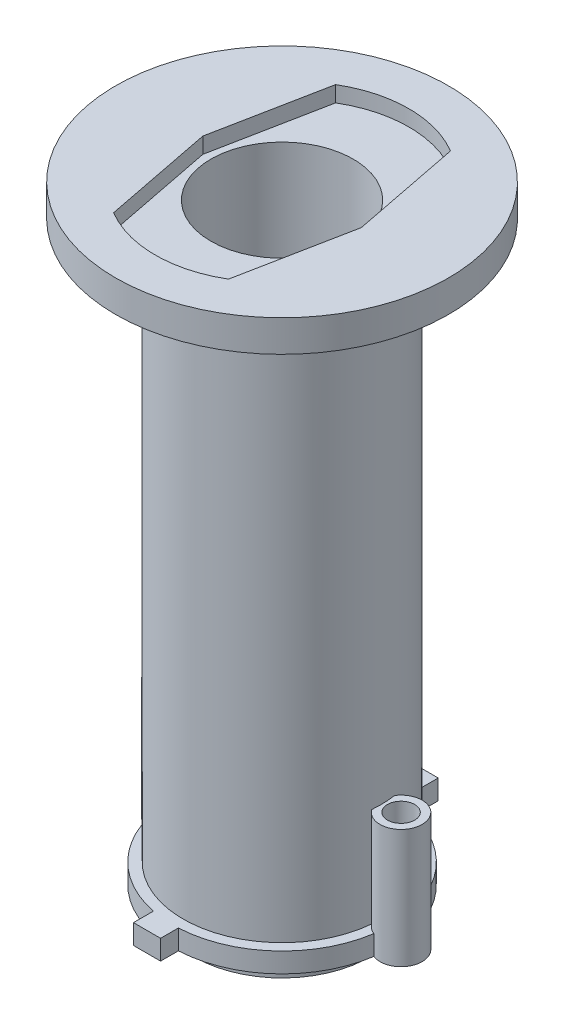
SolidWorks part; units mm, degrees
material "ABS"
ref_plane "Front Plane" through (0, 0, 0) normal (0, 0, 1) x (1, 0, 0)
ref_plane "Top Plane" through (0, 0, 0) normal (0, 1, 0) x (1, 0, 0)
ref_plane "Right Plane" through (0, 0, 0) normal (1, 0, 0) x (0, 0, -1)
sketch "Sketch1" plane through (0, 0, 0) normal (0, 1, 0) x (1, 0, 0)
  line L0 (14.5034, -1.0795) -> (-14.5034, -1.0795) construction
  line L1 (0.598, 12.2364) -> (0.598, 17.5133)
  line L2 (0.598, 17.5133) -> (-2.8194, 17.5133)
  line L3 (-2.8194, 17.5133) -> (-2.8194, 11.9769)
  line L4 (-2.8194, -15.0046) -> (-2.8194, -17.5133)
  line L5 (-2.8194, -17.5133) -> (0.598, -17.5133)
  line L6 (0.598, -17.5133) -> (0.598, -15.2641)
  arc A0 (-2.8194, 11.9769) -> (-13.533, 1.3911) centre (-0.0762, -1.5138) ccw
  arc A1 (-13.533, 1.3911) -> (-13.6834, -3.604) centre (-14.5034, -1.0795) ccw
  arc A2 (-13.6834, -3.604) -> (-2.8194, -15.0046) centre (-0.0762, -1.5138) ccw
  arc A3 (0.598, -15.2641) -> (13.5388, -3.5523) centre (-0.0762, -1.5138) ccw
  arc A4 (13.5388, -3.5523) -> (13.3933, 1.3315) centre (14.5034, -1.0795) ccw
  arc A5 (13.3933, 1.3315) -> (0.598, 12.2364) centre (-0.0762, -1.5138) ccw
  dimension "D1" = 13.7668
  dimension "D2" = 2.6543
  dimension "D6" = 13.7668
  dimension "D15" = 2.6543
  dimension "D3" = 2.5087
  dimension "D4" = 2.2492
  dimension "D5" = 3.4174
  dimension "D7" = 14.5796
  dimension "D8" = 14.4272
  dimension "D9" = 5.2769
  dimension "D10" = 5.5364
  dimension "D11" = 3.4174
  dimension "D12" = 0.6742
  dimension "D13" = 2.7432
  dimension "D14" = 0.4343
extrude "Boss-Extrude1" add sketch "Sketch1" along normal blind 2.5
sketch "Sketch2" plane through (0, 2.5, 0) normal (0, 1, 0) x (1, 0, 0)
  circle A1 centre (-14.5034, -1.0795) radius 1.715
  circle A2 centre (14.5034, -1.0795) radius 1.715
  circle A3 centre (-0.0762, -1.5138) radius 8.98
  dimension "D1" = 3.43
  dimension "D2" = 3.43
  dimension "D3" = 17.96
extrude "Cut-Extrude1" cut sketch "Sketch2" against normal up to next contours A1 | A2 | A3
sketch "Sketch3" plane through (0, 2.5, 0) normal (0, 1, 0) x (1, 0, 0)
  circle A0 centre (-14.5034, -1.0795) radius 2.6543
  circle A1 centre (14.5034, -1.0795) radius 2.6543
extrude "Boss-Extrude2" add sketch "Sketch3" along normal blind 70.305
sketch "Sketch4" plane through (0, 72.805, 0) normal (0, 1, 0) x (1, 0, 0)
  circle A0 centre (-0.0762, -1.5138) radius 8.98
  circle A1 centre (-0.0762, -1.5138) radius 21
  dimension "D1" = 42
extrude "Boss-Extrude3" add sketch "Sketch4" along normal blind 4
sketch "Sketch5" plane through (0, 76.805, 0) normal (0, 1, 0) x (1, 0, 0)
  line L0 (-0.0762, -1.5104) -> (-7.4262, -1.5104) construction
  line L1 (-7.4262, 12.1396) -> (-10.0762, -1.5104)
  line L2 (-10.0762, -1.5104) -> (-7.4262, -15.1604)
  line L3 (7.2738, -15.1604) -> (9.9238, -1.5104)
  line L4 (9.9238, -1.5104) -> (7.2738, 12.1396)
  circle A0 centre (-0.0762, -1.5104) radius 21
  arc A1 (-7.4262, 12.1396) -> (7.2738, 12.1396) centre (-0.0762, -1.5069) cw
  arc A2 (-7.4262, -15.1604) -> (7.2738, -15.1604) centre (-0.0762, -1.5138) ccw
  point P11 (-0.0762, -1.5138)
  dimension "D5" = 15.5
  dimension "D6" = 15.5
  dimension "D1" = 14.7
  dimension "D2" = 27.3
  dimension "D3" = 10
  dimension "D4" = 10
ref_plane "Plane1" through (0, 37.805, 0) normal (0, -1, 0) x (-1, 0, 0)
sketch "Sketch6" plane through (0, 37.805, 0) normal (0, -1, 0) x (-1, 0, 0)
  circle A0 centre (0.0762, -1.5138) radius 21
  circle A1 centre (0.0762, -1.5138) radius 8.98
extrude "Boss-Extrude4" add sketch "Sketch6" along normal blind 2
sketch "Sketch7" plane through (0, 0, 0) normal (0, -1, 0) x (1, 0, 0)
  circle A0 centre (-14.5034, 1.0795) radius 1.715
  circle A1 centre (14.5034, 1.0795) radius 1.715
extrude "Cut-Extrude3" cut sketch "Sketch7" against normal blind 15
sketch "Sketch8" plane through (0, 76.805, 0) normal (0, 1, 0) x (1, 0, 0)
  line L0 (-10.0762, -1.5138) -> (9.9238, -1.5138) construction
  line L1 (9.9238, -17.5138) -> (-10.0762, -17.5138) construction
  line L2 (9.9238, -17.5138) -> (9.9238, 14.4862) construction
  line L3 (9.9238, 14.4862) -> (-10.0762, 14.4862) construction
  line L4 (-10.0762, -17.5138) -> (-10.0762, 14.4862) construction
  line L5 (9.9238, -17.5138) -> (-10.0762, 14.4862) construction
  line L6 (9.9238, 14.4862) -> (-10.0762, -17.5138) construction
  line L7 (7.1738, -15.5138) -> (-7.3262, -15.5138) construction
  line L8 (7.1738, -15.5138) -> (7.1738, 12.4862) construction
  line L9 (7.1738, 12.4862) -> (-7.3262, 12.4862) construction
  line L10 (-7.3262, -15.5138) -> (-7.3262, 12.4862) construction
  line L11 (7.1738, -15.5138) -> (-7.3262, 12.4862) construction
  line L12 (7.1738, 12.4862) -> (-7.3262, -15.5138) construction
  line L13 (-10.0762, -1.5138) -> (-7.3262, -15.5138)
  line L14 (7.1738, -15.5138) -> (9.9238, -1.5138)
  line L15 (9.9238, -1.5138) -> (7.1738, 12.4862)
  line L16 (-7.3262, 12.4862) -> (-10.0762, -1.5138)
  circle A0 centre (-0.0762, -1.5138) radius 8.98
  arc A1 (-7.3262, 12.4862) -> (7.1738, 12.4862) centre (-0.0762, 0.3455) cw
  arc A2 (-7.3262, -15.5138) -> (7.1738, -15.5138) centre (-0.0762, -3.3732) ccw
  dimension "D1" = 32
  dimension "D2" = 20
  dimension "D3" = 14.5
  dimension "D4" = 28
extrude "Cut-Extrude4" cut sketch "Sketch8" against normal blind 2
sketch "Sketch9" plane through (0, 0, 0) normal (0, -1, 0) x (1, 0, 0)
  circle A0 centre (-0.0762, 1.5138) radius 8.9789
  circle A1 centre (-0.0762, 1.5138) radius 11.0744
  circle A2 centre (-0.0762, 1.5138) radius 8.98
  circle M2 centre (-0.0762, 1.5138) radius 8.98
extrude "Boss-Extrude5" add sketch "Sketch9" along normal blind 2.35 contours A1 M2
sketch "Sketch10" plane through (0, 2.5, 0) normal (0, 1, 0) x (1, 0, 0)
  circle A0 centre (-0.0762, -1.5138) radius 8.98
  circle A1 centre (-0.0762, -1.5138) radius 12.48
  dimension "D1" = 3.5
extrude "Boss-Extrude6" add sketch "Sketch10" along normal up to surface (70.305 mm away) up to face at (-14.5034, 72.805, 3.7338)
sketch "Sketch12" plane through (0, 15, 0) normal (0, -1, 0) x (1, 0, 0)
  circle A0 centre (-0.0762, 1.5138) radius 21
  circle A1 centre (-0.0762, 1.5138) radius 8.98 construction
  circle A2 centre (-0.0762, 1.5138) radius 12.48
  dimension "D1" = 3.5
extrude "Cut-Extrude5" cut sketch "Sketch12" against normal up to surface (57.805 mm away) up to face at (-0.0762, 72.805, 22.5138)
